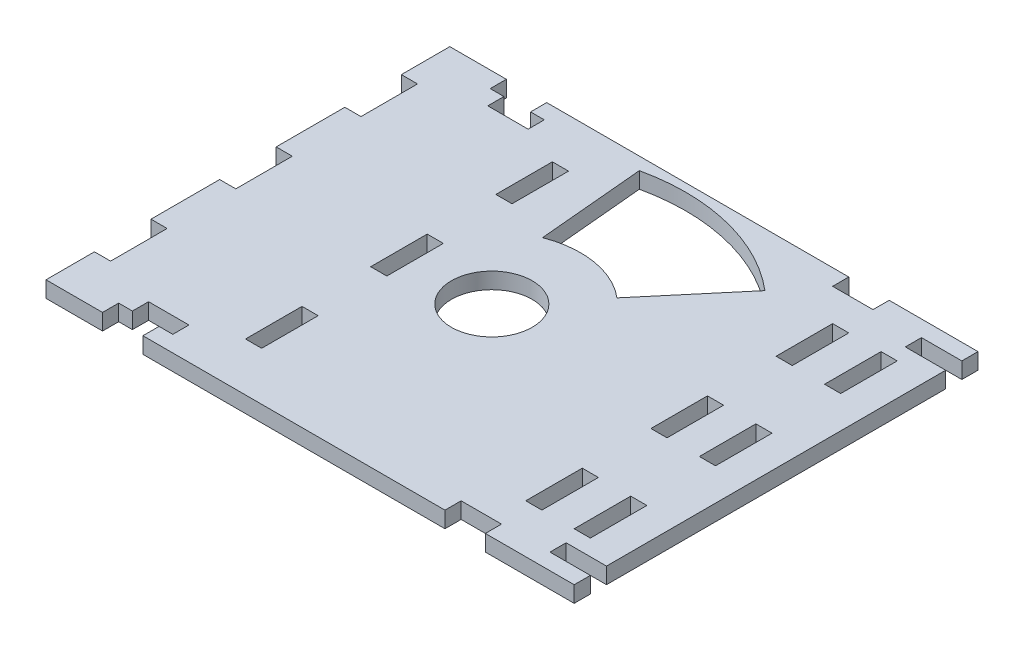
SolidWorks part; units mm, degrees
ref_plane "Front Plane" through (0, 0, 0) normal (0, 0, 1) x (1, 0, 0)
ref_plane "Top Plane" through (0, 0, 0) normal (0, 1, 0) x (1, 0, 0)
ref_plane "Right Plane" through (0, 0, 0) normal (1, 0, 0) x (0, 0, -1)
sketch "Sketch2" plane through (0, 0, 0) normal (0, 1, 0) x (1, 0, 0)
  line L1 (-50, 25) -> (50, 25)
  line L2 (-50, 25) -> (-50, -25)
  line L3 (-50, -25) -> (50, -25)
  line L4 (50, 25) -> (50, -25)
  line L5 (-50, 25) -> (50, -25) construction
  line L6 (-50, -25) -> (50, 25) construction
  circle A0 centre (0, 0) radius 5
  point P0 (0, 0)
  dimension "D3" = 10
  dimension "D1" = 100
  dimension "D2" = 50
extrude "Boss-Extrude1" add sketch "Sketch2" along normal blind 2
sketch "Sketch5" plane through (0, 0, 0) normal (0, -1, 0) x (-1, 0, 0)
  line L0 (-50, 25) -> (50, 25) construction
  line L1 (-23.2, -19) -> (-25.2, -19)
  line L2 (-23.2, -19) -> (-23.2, -12)
  line L3 (-23.2, -12) -> (-25.2, -12)
  line L4 (-25.2, -19) -> (-25.2, -12)
  line L5 (-23.2, -3.5) -> (-25.2, -3.5)
  line L6 (-23.2, -3.5) -> (-23.2, 3.5)
  line L7 (-23.2, 3.5) -> (-25.2, 3.5)
  line L8 (-25.2, -3.5) -> (-25.2, 3.5)
  line L9 (-23.2, 12) -> (-25.2, 12)
  line L10 (-23.2, 12) -> (-23.2, 19)
  line L11 (-23.2, 19) -> (-25.2, 19)
  line L12 (-25.2, 12) -> (-25.2, 19)
  line L13 (11.5, 12) -> (9.5, 12)
  line L14 (11.5, 12) -> (11.5, 19)
  line L15 (11.5, 19) -> (9.5, 19)
  line L16 (9.5, 12) -> (9.5, 19)
  line L17 (11.5, -3.5) -> (9.5, -3.5)
  line L18 (11.5, -3.5) -> (11.5, 3.5)
  line L19 (11.5, 3.5) -> (9.5, 3.5)
  line L20 (9.5, -3.5) -> (9.5, 3.5)
  line L21 (11.5, -19) -> (9.5, -19)
  line L22 (11.5, -19) -> (11.5, -12)
  line L23 (11.5, -12) -> (9.5, -12)
  line L24 (9.5, -19) -> (9.5, -12)
  line L25 (50, -25) -> (-50, -25) construction
  line L26 (-50, 25) -> (50, 25) construction
  line L27 (50, -25) -> (-50, -25) construction
  point P29 (-24.2, -19)
  dimension "D1" = 2
  dimension "D2" = 7
  dimension "D3" = 7
  dimension "D4" = 7
  dimension "D5" = 2
  dimension "D6" = 2
  dimension "D7" = 2
  dimension "D8" = 2
  dimension "D9" = 2
  dimension "D10" = 7
  dimension "D11" = 7
  dimension "D12" = 7
  dimension "D13" = 6
  dimension "D14" = 8.5
  dimension "D15" = 8.5
  dimension "D16" = 6
  dimension "D17" = 6
  dimension "D18" = 8.5
  dimension "D19" = 8.5
  dimension "D20" = 6
  dimension "D21" = 9.5
  dimension "D22" = 0
  dimension "D23" = 32.7
  dimension "D24" = 0
  dimension "D25" = 0
  dimension "D26" = 0
  dimension "D27" = 32.7
extrude "Cut-Extrude3" cut sketch "Sketch5" against normal blind 2
sketch "Sketch10" plane through (0, 2, 0) normal (0, 1, 0) x (1, 0, 0)
  line L0 (-5.1716, 23.4362) -> (-3.9753, 10.2565)
  line L1 (15.4739, 18.3455) -> (7.0922, 8.4084)
  arc A0 (-3.9753, 10.2565) -> (7.0922, 8.4084) centre (0, 0) cw
  arc A1 (-5.1716, 23.4362) -> (15.4739, 18.3455) centre (0, 0) cw
  dimension "D1" = 24
  dimension "D2" = 11
extrude "Cut-Extrude6" cut sketch "Sketch10" against normal blind 2 contours A1 L0 A0 L1
sketch "Sketch11" plane through (0, 2, 0) normal (0, 1, 0) x (1, 0, 0)
  line L0 (-50, -25) -> (50, -25) construction
  line L1 (-21.5, -25) -> (-16.5, -25)
  line L2 (-21.5, -25) -> (-21.5, -23)
  line L3 (-21.5, -23) -> (-16.5, -23)
  line L4 (-16.5, -25) -> (-16.5, -23)
  line L5 (50, 25) -> (-50, 25) construction
  line L6 (35.2, -25) -> (30.2, -25)
  line L7 (35.2, -25) -> (35.2, -23)
  line L8 (35.2, -23) -> (30.2, -23)
  line L9 (30.2, -25) -> (30.2, -23)
  line L10 (35.2, 25) -> (30.2, 25)
  line L11 (35.2, 25) -> (35.2, 23)
  line L12 (35.2, 23) -> (30.2, 23)
  line L13 (30.2, 25) -> (30.2, 23)
  line L15 (-21.5, 25) -> (-16.5, 25)
  line L16 (-21.5, 25) -> (-21.5, 23)
  line L17 (-21.5, 23) -> (-16.5, 23)
  line L18 (-16.5, 25) -> (-16.5, 23)
  line L19 (35.2, 23) -> (30.2, 23)
  line L20 (35.2, 23) -> (35.2, 21)
  line L21 (35.2, 21) -> (30.2, 21)
  line L22 (30.2, 23) -> (30.2, 21)
  line L23 (-16.5, 23) -> (-21.5, 23)
  line L24 (-16.5, 23) -> (-16.5, 21)
  line L25 (-16.5, 21) -> (-21.5, 21)
  line L26 (-21.5, 23) -> (-21.5, 21)
  line L27 (-16.5, -23) -> (-21.5, -23)
  line L28 (-16.5, -23) -> (-16.5, -21)
  line L29 (-16.5, -21) -> (-21.5, -21)
  line L30 (-21.5, -23) -> (-21.5, -21)
  line L31 (35.2, -23) -> (30.2, -23)
  line L32 (35.2, -23) -> (35.2, -21)
  line L33 (35.2, -21) -> (30.2, -21)
  line L34 (30.2, -23) -> (30.2, -21)
  dimension "D1" = 2
  dimension "D2" = 2
  dimension "D3" = 2
  dimension "D4" = 2
  dimension "D5" = 5
  dimension "D6" = 5
  dimension "D7" = 5
  dimension "D8" = 5
  dimension "D9" = 5
  dimension "D10" = 5
  dimension "D11" = 5
  dimension "D12" = 5
  dimension "D13" = 2
  dimension "D14" = 2
  dimension "D15" = 2
  dimension "D16" = 2
extrude "Cut-Extrude7" cut sketch "Sketch11" against normal blind 2 contours L12 L22 L21 L20 | L17 L26 L25 L24 | L30 L3 L28 L29 | L34 L8 L32 L33
sketch "Sketch12" plane through (0, 2, 0) normal (0, 1, 0) x (1, 0, 0)
  line L0 (-50, -25) -> (50, -25) construction
  line L1 (-43.5, -25) -> (-50, -25)
  line L2 (-43.5, -25) -> (-43.5, 25)
  line L3 (-43.5, 25) -> (-50, 25)
  line L4 (-50, -25) -> (-50, 25)
  line L5 (-50, -25) -> (50, -25) construction
  line L6 (47.2, -25) -> (50, -25)
  line L7 (47.2, -25) -> (47.2, 25)
  line L8 (47.2, 25) -> (50, 25)
  line L9 (50, -25) -> (50, 25)
  line L11 (35.2, 23) -> (35.2, 21) construction
  line L12 (-21.5, 23) -> (-21.5, 21) construction
  dimension "D1" = 12
  dimension "D2" = 22
extrude "Cut-Extrude8" cut sketch "Sketch12" against normal blind 6
sketch "Sketch13" plane through (0, 2, 0) normal (0, 1, 0) x (1, 0, 0)
  line L0 (35.2, 25) -> (35.2, -25)
  line L1 (-28.2, 19) -> (-30.2, 19)
  line L2 (-28.2, 19) -> (-28.2, 12)
  line L3 (-28.2, 12) -> (-30.2, 12)
  line L4 (-30.2, 19) -> (-30.2, 12)
  line L5 (-28.2, 3.5) -> (-30.2, 3.5)
  line L6 (-28.2, 3.5) -> (-28.2, -3.5)
  line L7 (-28.2, -3.5) -> (-30.2, -3.5)
  line L8 (-30.2, 3.5) -> (-30.2, -3.5)
  line L9 (-28.2, -12) -> (-30.2, -12)
  line L10 (-28.2, -12) -> (-28.2, -19)
  line L11 (-28.2, -19) -> (-30.2, -19)
  line L12 (-30.2, -12) -> (-30.2, -19)
  line L13 (29.2, 19) -> (31.2, 19)
  line L14 (29.2, 19) -> (29.2, 12)
  line L15 (29.2, 12) -> (31.2, 12)
  line L16 (31.2, 19) -> (31.2, 12)
  line L17 (29.2, 3.5) -> (31.2, 3.5)
  line L18 (29.2, 3.5) -> (29.2, -3.5)
  line L19 (29.2, -3.5) -> (31.2, -3.5)
  line L20 (31.2, 3.5) -> (31.2, -3.5)
  line L21 (29.2, -12) -> (31.2, -12)
  line L22 (29.2, -12) -> (29.2, -19)
  line L23 (29.2, -19) -> (31.2, -19)
  line L24 (31.2, -12) -> (31.2, -19)
  line L26 (47.2, 25) -> (-43.5, 25) construction
  line L27 (47.2, 25) -> (-43.5, 25) construction
  line L28 (-43.5, -25) -> (47.2, -25) construction
  line L29 (47.2, 25) -> (-43.5, 25) construction
  line L30 (-43.5, -25) -> (47.2, -25) construction
  line L31 (-43.5, -25) -> (-30.2, -25)
  line L32 (-43.5, -25) -> (-43.5, 25)
  line L33 (-43.5, 25) -> (-30.2, 25)
  line L34 (-30.2, -25) -> (-30.2, 25)
  line L35 (47.2, -25) -> (31.2, -25)
  line L36 (47.2, -25) -> (47.2, 25)
  line L37 (47.2, 25) -> (31.2, 25)
  line L38 (31.2, -25) -> (31.2, 25)
  line L39 (24.2, -25) -> (19.2, -25)
  line L40 (24.2, -25) -> (24.2, -23)
  line L41 (24.2, -23) -> (19.2, -23)
  line L42 (19.2, -25) -> (19.2, -23)
  line L43 (24.2, 23) -> (19.2, 23)
  line L44 (24.2, 23) -> (24.2, 25)
  line L45 (24.2, 25) -> (19.2, 25)
  line L46 (19.2, 23) -> (19.2, 25)
  line L48 (-23.2, 25) -> (-18.2, 25)
  line L49 (-23.2, 25) -> (-23.2, 23)
  line L50 (-23.2, 23) -> (-18.2, 23)
  line L51 (-18.2, 25) -> (-18.2, 23)
  line L52 (-23.2, -25) -> (-18.2, -25)
  line L53 (-23.2, -25) -> (-23.2, -23)
  line L54 (-23.2, -23) -> (-18.2, -23)
  line L55 (-18.2, -25) -> (-18.2, -23)
  point P30 (30.2, 3.5)
  line M32 (47.2, -25) -> (47.2, 25)
  line M39 (-21.5, 23) -> (-16.5, 23)
  line M41 (47.2, 25) -> (-43.5, 25)
  line M42 (-43.5, 25) -> (-43.5, -25)
  line M45 (-16.5, -23) -> (-21.5, -23)
  line M47 (-43.5, -25) -> (47.2, -25)
  line M120 (35.2, 23) -> (35.2, 21)
  line M125 (35.2, -21) -> (35.2, -23)
  dimension "D1" = 2
  dimension "D2" = 2
  dimension "D3" = 2
  dimension "D4" = 2
  dimension "D5" = 2
  dimension "D6" = 2
  dimension "D7" = 57.4
  dimension "D8" = 57.4
  dimension "D9" = 57.4
  dimension "D10" = 7
  dimension "D11" = 7
  dimension "D12" = 7
  dimension "D13" = 7
  dimension "D14" = 7
  dimension "D15" = 7
  dimension "D16" = 5
  dimension "D17" = 5
  dimension "D18" = 5
  dimension "D19" = 6
  dimension "D20" = 8.5
  dimension "D21" = 8.5
  dimension "D22" = 6
  dimension "D23" = 6
  dimension "D24" = 8.5
  dimension "D25" = 8.5
  dimension "D26" = 6
  dimension "D27" = 5
  dimension "D28" = 2
  dimension "D29" = 2
  dimension "D30" = 2
  dimension "D31" = 2
  dimension "D32" = 5
  dimension "D33" = 5
  dimension "D34" = 5
  dimension "D35" = 5
extrude "Cut-Extrude10" cut sketch "Sketch13" against normal blind 6 contours L0 M41 M120 M125 M47 M32 | L42 L40 L41 M47 | L24 L21 L22 L23 | L20 L17 L18 L19 | L16 L13 L14 L15 | L51 L49 L50 M41 M39 | L55 L54 L53 M47 M45 | L5 L8 L7 L6 | L1 L4 L3 L2 | L34 L12 L8 L4 M47 M41 M42 | L45 L46 L43 L44
